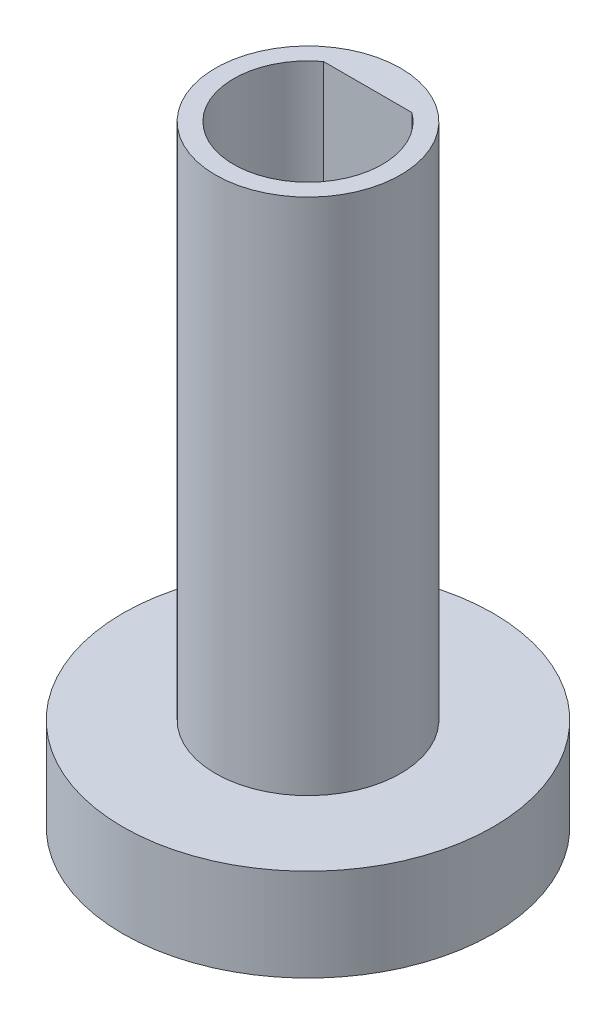
SolidWorks part; units mm, degrees
ref_plane "Front Plane" through (0, 0, 0) normal (0, 0, 1) x (1, 0, 0)
ref_plane "Top Plane" through (0, 0, 0) normal (0, 1, 0) x (1, 0, 0)
ref_plane "Right Plane" through (0, 0, 0) normal (1, 0, 0) x (0, 0, -1)
sketch "Sketch1" plane through (0, 0, 0) normal (0, 1, 0) x (1, 0, 0)
  circle A0 centre (0, 0) radius 6.35
  dimension "D1" = 12.7
extrude "Boss-Extrude1" add sketch "Sketch1" along normal blind 3.175
sketch "Sketch2" plane through (0, 3.175, 0) normal (0, 1, 0) x (1, 0, 0)
  circle A0 centre (0, 0) radius 3.175
  dimension "D1" = 6.35
extrude "Boss-Extrude2" add sketch "Sketch2" along normal blind 17.78
sketch "Sketch3" plane through (0, 20.955, 0) normal (0, 1, 0) x (1, 0, 0)
  line L0 (0, 0) -> (-2.55, 0) construction
  line L1 (-2.55, 0) -> (2.55, 0) construction
  line L2 (0, -2.55) -> (0, 2.05) construction
  line L3 (-1.5166, 2.05) -> (1.5166, 2.05)
  arc A0 (-1.5166, 2.05) -> (1.5166, 2.05) centre (0, 0) ccw
  dimension "D1" = 5.1
  dimension "D2" = 4.6
extrude "Cut-Extrude1" cut sketch "Sketch3" against normal up to surface (17.78 mm away) up to face at (0, 3.175, 3.175)
sketch "Sketch4" plane through (0, 0, 0) normal (0, -1, 0) x (1, 0, 0)
  circle A0 centre (0, 0) radius 0.762
extrude "Cut-Extrude2" cut sketch "Sketch4" against normal through all
